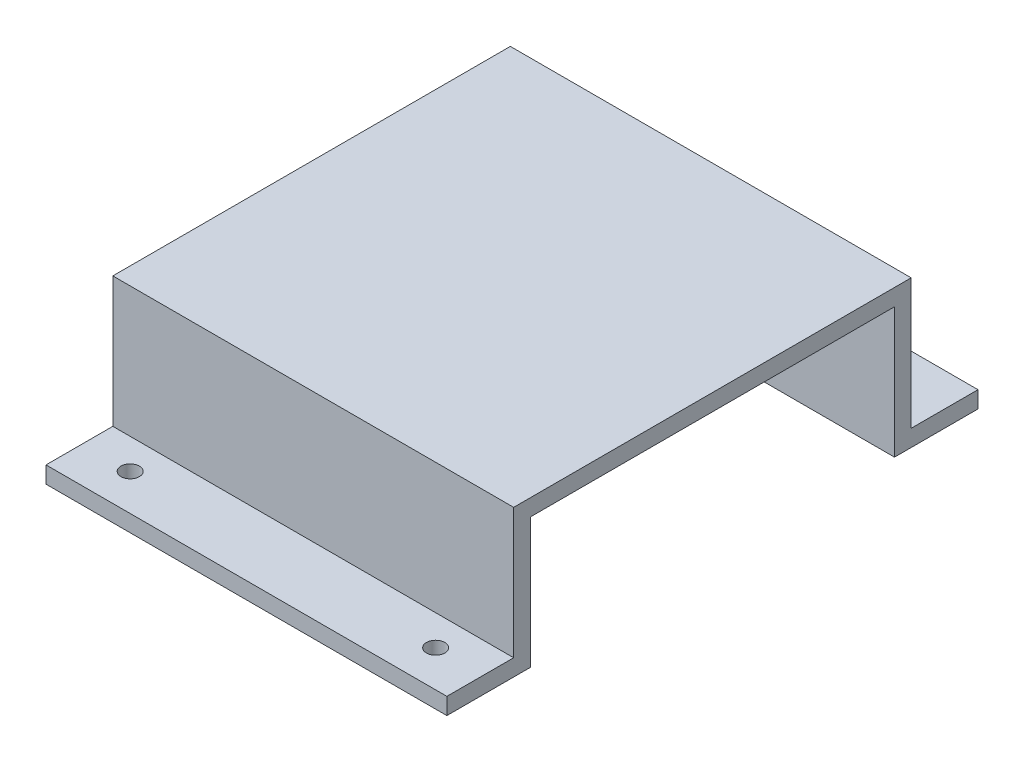
SolidWorks part; units mm, degrees
ref_plane "Front Plane" through (0, 0, 0) normal (1, 0, 0) x (0, 1, 0)
ref_plane "Top Plane" through (0, 0, 0) normal (0, 0, 1) x (0, 1, 0)
ref_plane "Right Plane" through (0, 0, 0) normal (0, 1, 0) x (-1, 0, 0)
sketch "Sketch1" plane through (0, 0, 0) normal (1, 0, 0) x (0, 1, 0)
  line L14 (39, 0) -> (39, 54.5)
  line L15 (39, 54.5) -> (0, 54.5)
  line L16 (0, 54.5) -> (0, 79.5)
  line L17 (44, 0) -> (44, 59.5)
  line L18 (44, 59.5) -> (5, 59.5)
  line L19 (5, 59.5) -> (5, 79.5)
  line L20 (0, 79.5) -> (5, 79.5)
  line L21 (23.65, 0) -> (-23.65, 0) construction
  line L22 (0, -79.5) -> (5, -79.5)
  line L23 (5, -59.5) -> (5, -79.5)
  line L24 (44, -59.5) -> (5, -59.5)
  line L25 (44, 0) -> (44, -59.5)
  line L26 (0, -54.5) -> (0, -79.5)
  line L27 (39, -54.5) -> (0, -54.5)
  line L28 (39, 0) -> (39, -54.5)
  dimension "D1" = 39
  dimension "D2" = 54.5
  dimension "D3" = 25
  dimension "D4" = 5
extrude "Boss-Extrude1" add sketch "Sketch1" along normal mid plane 120
sketch "Sketch2" plane through (0, 5, 0) normal (0, 1, 0) x (-1, 0, 0)
  line L1 (-45.72, -68.58) -> (-45.72, 68.58) construction
  line L2 (-45.72, 68.58) -> (45.72, 68.58) construction
  line L3 (45.72, 68.58) -> (45.72, -68.58) construction
  line L4 (45.72, -68.58) -> (-45.72, -68.58) construction
  circle A0 centre (-45.72, 68.58) radius 2.75
  circle A1 centre (45.72, 68.58) radius 2.75
  circle A2 centre (45.72, -68.58) radius 2.75
  circle A3 centre (-45.72, -68.58) radius 2.75
  point P2 (-45.72, 0)
  point P3 (0, 68.58)
  dimension "D1" = 137.16
  dimension "D4" = 5.5
  dimension "D5" = 91.44
  dimension "D2" = 2
  dimension "D3" = 2
extrude "Cut-Extrude1" cut sketch "Sketch2" against normal through all
